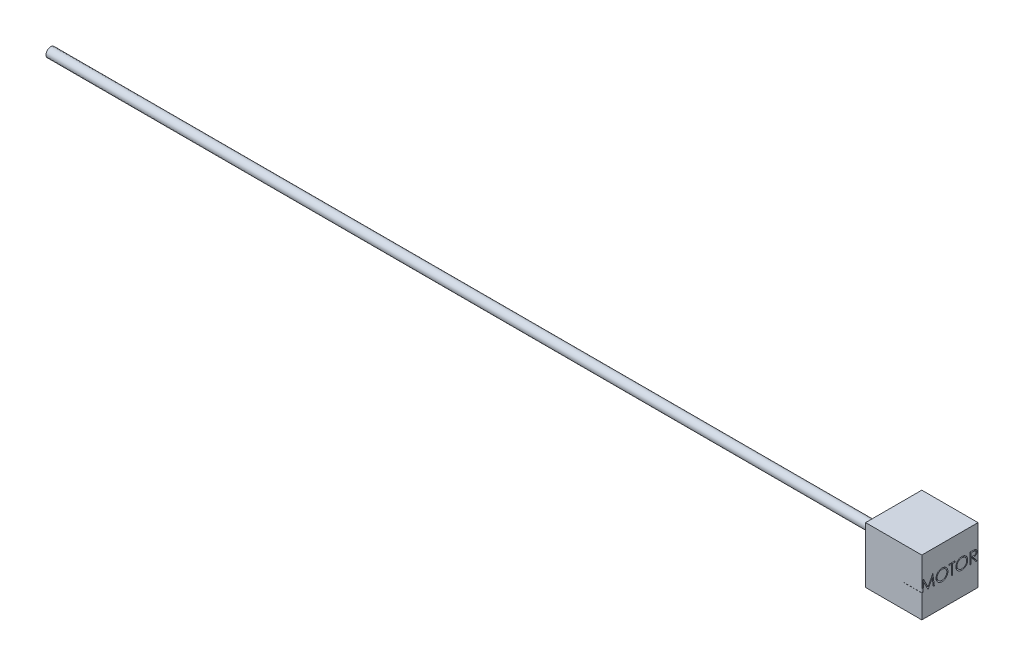
SolidWorks part; units mm, degrees
ref_plane "Front Plane" through (0, 0, 0) normal (0, 0, 1) x (1, 0, 0)
ref_plane "Top Plane" through (0, 0, 0) normal (0, 1, 0) x (1, 0, 0)
ref_plane "Right Plane" through (0, 0, 0) normal (1, 0, 0) x (0, 0, -1)
sketch "Sketch1" plane through (0, 0, 0) normal (1, 0, 0) x (0, 0, -1)
  line L1 (0, 0) -> (30, 0)
  line L2 (0, 0) -> (0, 30)
  line L3 (0, 30) -> (30, 30)
  line L4 (30, 0) -> (30, 30)
  dimension "D1" = 30
  dimension "D2" = 30
extrude "MotorBody" add sketch "Sketch1" against normal blind 30
sketch "Sketch2" plane through (0, 0, 0) normal (1, 0, 0) x (0, 0, -1)
  text T0 "MOTOR" font "Century Gothic" height 6
  point P1 (7.8335, 13.0821)
  point P2 (0, 0)
  point P3 (1.2644, 12.3669)
  point P4 (0, 0)
  point P5 (-0.4692, 12.4709)
extrude "MotorLetter" cut sketch "Sketch2" against normal blind 10
sketch "Sketch3" plane through (-30, 0, 0) normal (-1, 0, 0) x (0, 0, 1)
  line L0 (-30, 0) -> (0, 30) construction
  circle A0 centre (-15, 15) radius 2.5
  dimension "D1" = 5
extrude "ThreadedRod" add sketch "Sketch3" along normal blind 450
